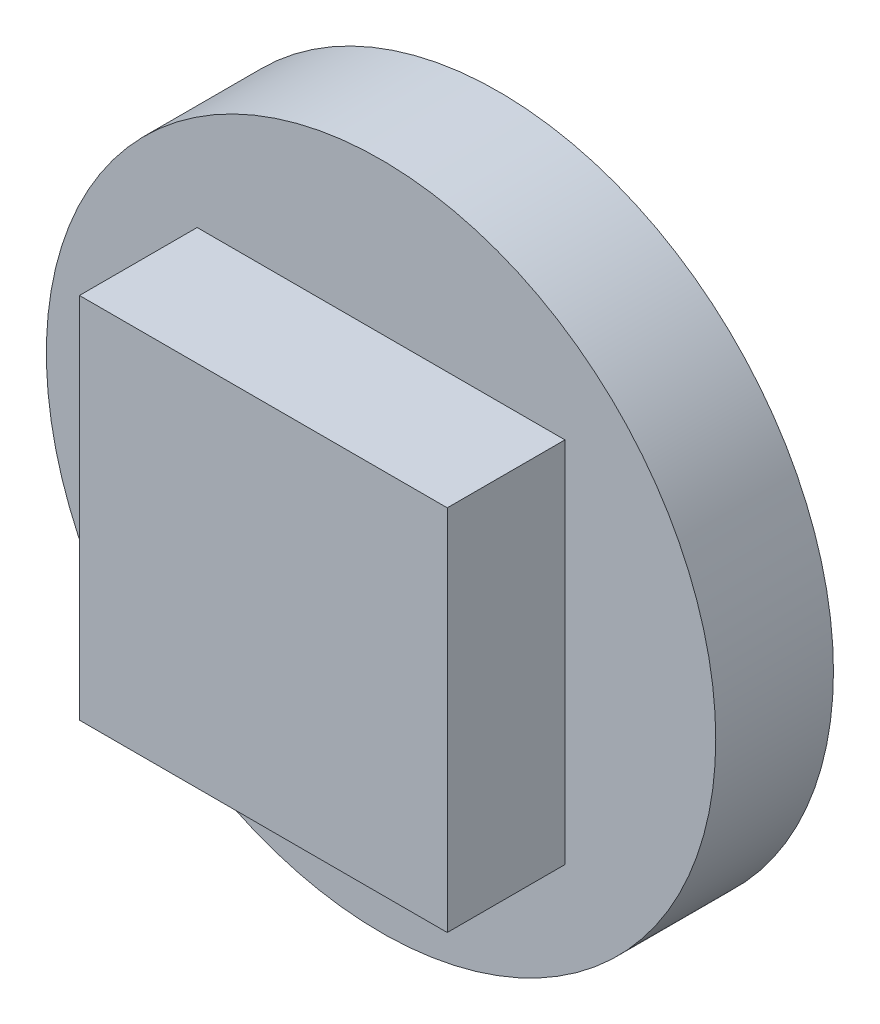
SolidWorks part; units mm, degrees
ref_plane "Front Plane" through (0, 0, 0) normal (0, 0, 1) x (1, 0, 0)
ref_plane "Top Plane" through (0, 0, 0) normal (0, 1, 0) x (1, 0, 0)
ref_plane "Right Plane" through (0, 0, 0) normal (1, 0, 0) x (0, 0, -1)
sketch "Sketch1" plane through (0, 0, 0) normal (0, 0, 1) x (1, 0, 0)
  circle A0 centre (0, 0) radius 4.55
  dimension "D1" = 9.1
extrude "Boss-Extrude1" add sketch "Sketch1" along normal blind 1.6 contours A0
sketch "Sketch3" plane through (0, 0, 1.6) normal (0, 0, 1) x (1, 0, 0)
  line L1 (-2.5, 2.5) -> (2.5, 2.5)
  line L2 (-2.5, 2.5) -> (-2.5, -2.5)
  line L3 (-2.5, -2.5) -> (2.5, -2.5)
  line L4 (2.5, 2.5) -> (2.5, -2.5)
  line L5 (-2.5, 2.5) -> (2.5, -2.5) construction
  line L6 (-2.5, -2.5) -> (2.5, 2.5) construction
  point P0 (0, 0)
  dimension "D1" = 5
extrude "Boss-Extrude2" add sketch "Sketch3" along normal blind 1.6
